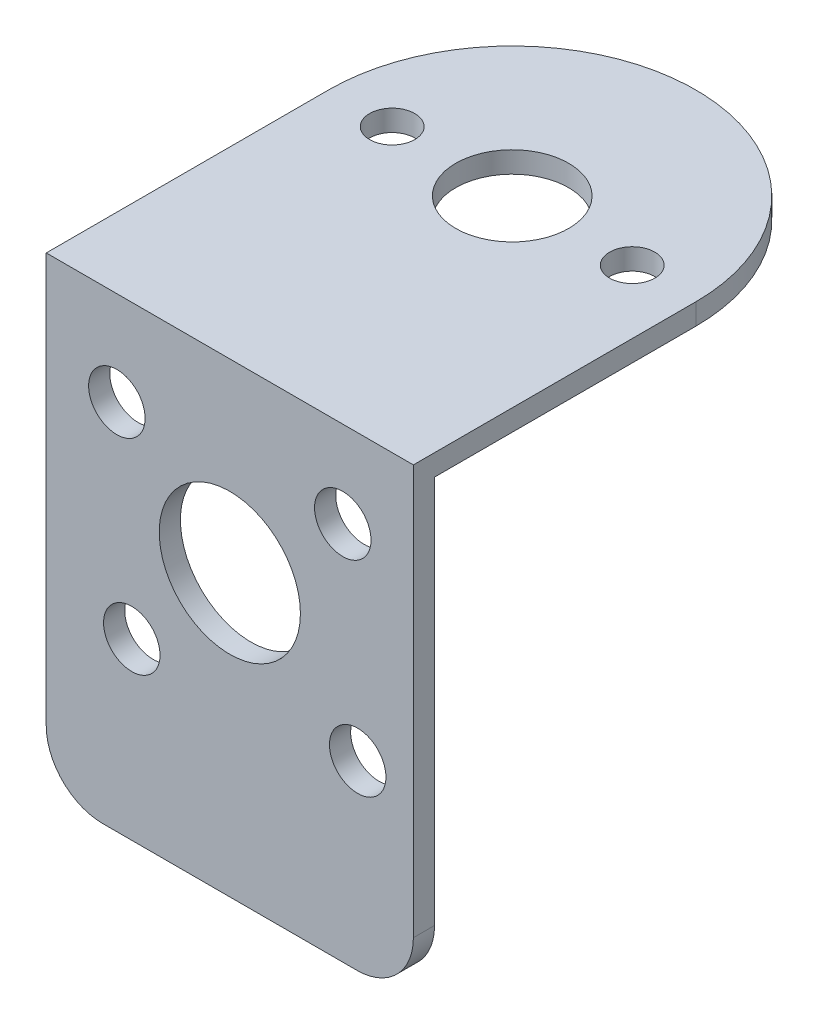
SolidWorks part; units mm, degrees
ref_plane "Front Plane" through (0, 0, 0) normal (0, 0, 1) x (1, 0, 0)
ref_plane "Top Plane" through (0, 0, 0) normal (0, 1, 0) x (1, 0, 0)
ref_plane "Right Plane" through (0, 0, 0) normal (1, 0, 0) x (0, 0, -1)
sketch "Sketch1" plane through (0, 0, 0) normal (0, 1, 0) x (1, 0, 0)
  line L0 (-13, -20) -> (-13, 0)
  line L1 (13, -20) -> (13, 0)
  line L2 (-13, -20) -> (13, -20)
  circle A0 centre (0, 0) radius 4
  arc A1 (13, 0) -> (-13, 0) centre (0, 0) ccw
  circle A2 centre (8.5, 0) radius 1.6
  circle A3 centre (-8.5, 0) radius 1.6
  point P3 (0, 13)
  dimension "D1" = 17
  dimension "D2" = 8.5
  dimension "D3" = 26
  dimension "D4" = 8
  dimension "D7" = 3.2
  dimension "D8" = 3.2
  dimension "D5" = 33
extrude "Boss-Extrude1" add sketch "Sketch1" against normal blind 1.5
sketch "Sketch2" plane through (0, 0, 20) normal (0, 0, 1) x (1, 0, 0)
  line L0 (13, -1.5) -> (13, -29)
  line L1 (-13, -1.5) -> (-13, -29)
  line L2 (-9, -33) -> (9, -33)
  line L3 (-13, -1.5) -> (13, -1.5) construction
  line L4 (-13, -1.5) -> (13, -1.5)
  circle A0 centre (0, -13.1222) radius 5
  circle A1 centre (8, -6.1222) radius 2
  circle A2 centre (-8, -6.6476) radius 2
  circle A3 centre (-6.9427, -20.6476) radius 2
  circle A4 centre (9.0573, -20.1222) radius 2
  arc A5 (-13, -29) -> (-9, -33) centre (-9, -29) ccw
  arc A6 (13, -29) -> (9, -33) centre (9, -29) cw
  point P19 (-13, -33)
  point P22 (13, -33)
  dimension "D1" = 10
  dimension "D2" = 4
  dimension "D3" = 4
  dimension "D4" = 4
  dimension "D5" = 4
  dimension "D6" = 16
  dimension "D7" = 14
  dimension "D8" = 14
  dimension "D9" = 16
  dimension "D10" = 7
  dimension "D11" = 8
  dimension "D14" = 4
  dimension "D15" = 4
  dimension "D12" = 31.5
  dimension "D13" = 31.5
extrude "Boss-Extrude2" add sketch "Sketch2" against normal blind 1.5
